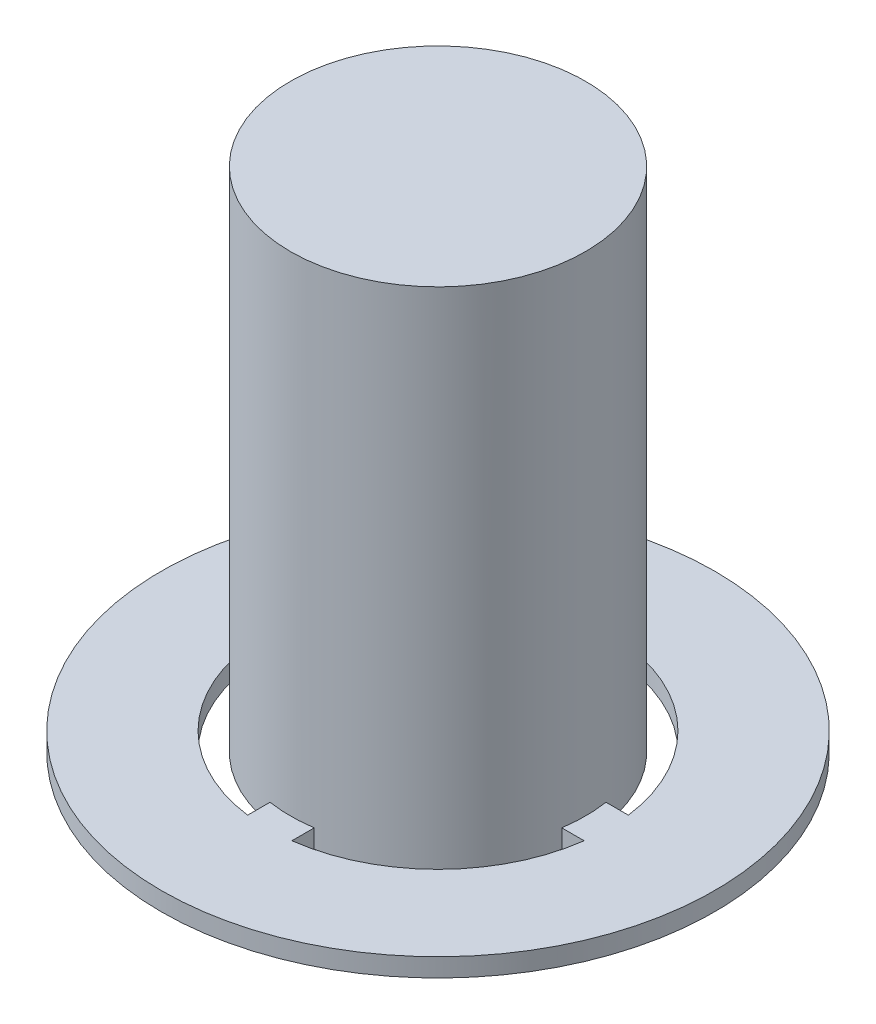
SolidWorks part; units mm, degrees
ref_plane "Front Plane" through (0, 0, 0) normal (0, 0, 1) x (1, 0, 0)
ref_plane "Top Plane" through (0, 0, 0) normal (0, 1, 0) x (1, 0, 0)
ref_plane "Right Plane" through (0, 0, 0) normal (1, 0, 0) x (0, 0, -1)
sketch "Sketch1" plane through (0, 0, 0) normal (0, 1, 0) x (1, 0, 0)
  circle A0 centre (0, 0) radius 4
  dimension "D1" = 8
extrude "Boss-Extrude1" add sketch "Sketch1" along normal blind 13.75
sketch "Sketch2" plane through (0, 0, 0) normal (0, -1, 0) x (-1, 0, 0)
  circle A0 centre (0, 0) radius 7.5
  circle A1 centre (0, 0) radius 4.6
  dimension "D1" = 9.2
  dimension "D2" = 15
extrude "Boss-Extrude2" add sketch "Sketch2" against normal blind 0.5 separate body
sketch "Sketch3" plane through (0, 0, 0) normal (0, -1, 0) x (-1, 0, 0)
  line L1 (6, 0.6) -> (-6, 0.6)
  line L2 (6, 0.6) -> (6, -0.6)
  line L3 (6, -0.6) -> (-6, -0.6)
  line L4 (-6, 0.6) -> (-6, -0.6)
  line L5 (6, 0.6) -> (-6, -0.6) construction
  line L6 (6, -0.6) -> (-6, 0.6) construction
  line L7 (0.6, 6) -> (-0.6, 6)
  line L8 (0.6, 6) -> (0.6, -6)
  line L9 (0.6, -6) -> (-0.6, -6)
  line L10 (-0.6, 6) -> (-0.6, -6)
  line L11 (0.6, 6) -> (-0.6, -6) construction
  line L12 (0.6, -6) -> (-0.6, 6) construction
  point P0 (0, 0)
  point P6 (0, 0)
  circle M1 centre (0, 0) radius 4
  dimension "D1" = 12
  dimension "D2" = 1.2
  dimension "D3" = 12
  dimension "D4" = 1.2
extrude "Boss-Extrude3" add sketch "Sketch3" against normal blind 0.5 contours L7 L10 L8 M1 | L10 L9 L8 M1 | L10 L1 L8 M1 | L3 L10 L8 M1
